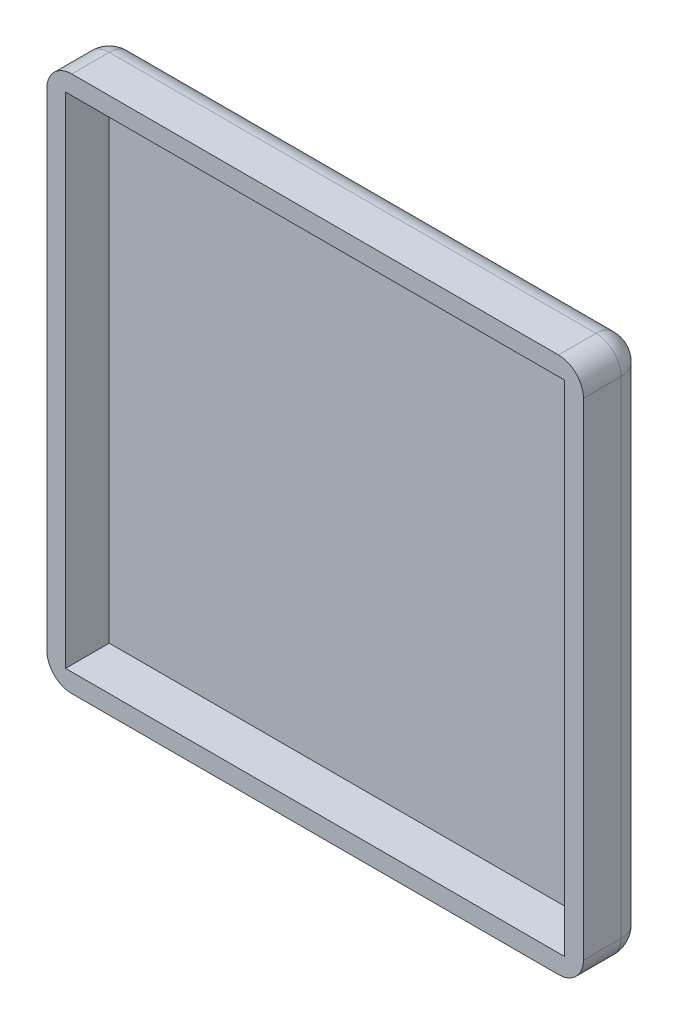
SolidWorks part; units mm, degrees
ref_plane "Ön Düzlem" through (0, 0, 0) normal (0, 0, 1) x (1, 0, 0)
ref_plane "Üst Düzlem" through (0, 0, 0) normal (0, 1, 0) x (1, 0, 0)
ref_plane "Sağ Düzlem" through (0, 0, 0) normal (1, 0, 0) x (0, 0, -1)
ref_plane "Düzlem1" through (0, 0, 5) normal (0, 0, 1) x (1, 0, 0)
sketch "Çizim1" plane through (0, 0, 5) normal (0, 0, 1) x (1, 0, 0)
  line L0 (-21.5, -21.5) -> (21.5, -21.5)
  line L1 (21.5, -21.5) -> (21.5, 21.5)
  line L2 (21.5, 21.5) -> (-21.5, 21.5)
  line L3 (-21.5, 21.5) -> (-21.5, -21.5)
extrude "Yükseklik-Ekstrüzyon1" add sketch "Çizim1" against normal blind 5
sketch "Çizim2" plane through (0, 0, 5) normal (0, 0, 1) x (1, 0, 0)
  line L0 (-20, -20) -> (20, -20)
  line L1 (20, -20) -> (20, 20)
  line L2 (20, 20) -> (-20, 20)
  line L3 (-20, 20) -> (-20, -20)
extrude "Kes-Ekstrüzyon1" cut sketch "Çizim2" against normal blind 3.5
fillet "Radyus1" radius 2 8 edges at (-21.5, -21.5, 2.5) (0, -21.5, 0) (21.5, -21.5, 2.5) (-21.5, 0, 0) (21.5, 21.5, 2.5) (-21.5, 21.5, 2.5) (21.5, 0, 0) (0, 21.5, 0)
